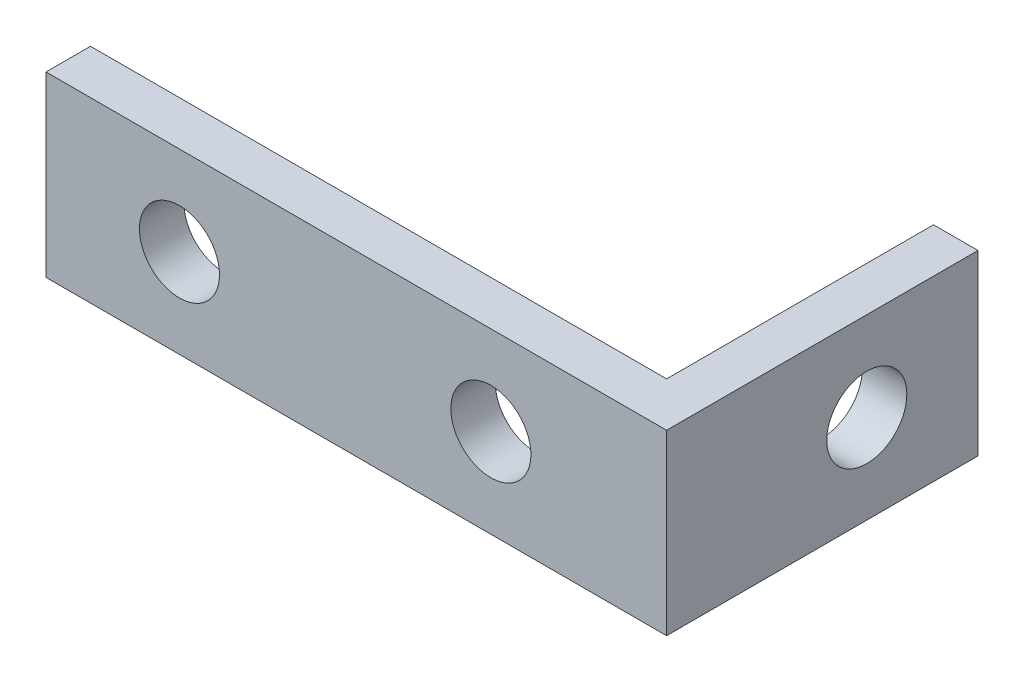
SolidWorks part; units mm, degrees
ref_plane "Front Plane" through (0, 0, 0) normal (0, 0, 1) x (1, 0, 0)
ref_plane "Top Plane" through (0, 0, 0) normal (0, 1, 0) x (1, 0, 0)
ref_plane "Right Plane" through (0, 0, 0) normal (1, 0, 0) x (0, 0, -1)
sketch "Sketch1" plane through (0, 74.0934, 0) normal (0, 1, 0) x (1, 0, 0)
  line L1 (-168.75, -59.5023) -> (-238.5, -59.5023)
  line L2 (-168.75, -59.5023) -> (-168.75, -94.5023)
  line L3 (-168.75, -94.5023) -> (-238.5, -94.5023)
  line L4 (-238.5, -59.5023) -> (-238.5, -94.5023)
  line L5 (-238.5, -94.5023) -> (-158.5, -94.5023) construction
  point P8 (-238.5, -94.5023)
  dimension "D1" = 35
extrude "Boss-Extrude1" add sketch "Sketch1" against normal blind 20
shell "Shell1" thickness 5
sketch "Sketch2" plane through (0, 0, 89.5023) normal (0, 0, -1) x (-1, 0, 0)
  circle A0 centre (188.5, 64.0934) radius 4.5
  circle A1 centre (223.5, 64.0934) radius 4.5
  dimension "D1" = 9
  dimension "D2" = 9
extrude "M8 clearance - 9 mm thru" cut sketch "Sketch2" against normal through all
sketch "Sketch3" plane through (-173.75, 0, 0) normal (-1, 0, 0) x (0, 0, 1)
  line L0 (72.0023, -201.526) -> (72.0023, 298.474) construction
  line L2 (59.5023, 64.0934) -> (87.5388, 64.0934) construction
  line L3 (59.5023, 54.0934) -> (59.5023, 74.0934) construction
  circle A0 centre (72.0023, 64.0934) radius 4.5
  dimension "D1" = 9
extrude "M8 Clearance - 9mm thru - 2" cut sketch "Sketch3" against normal through all
